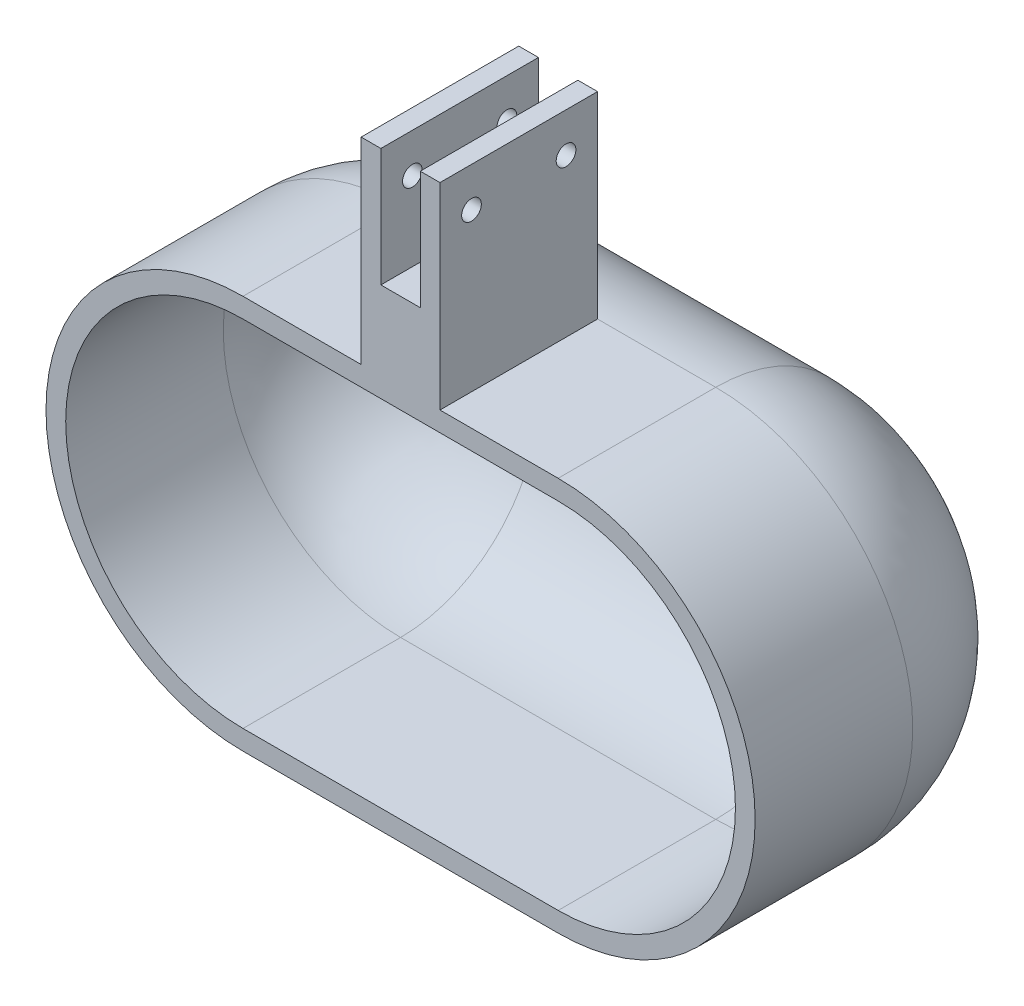
SolidWorks part; units mm, degrees
ref_plane "Front Plane" through (0, 0, 0) normal (0, 0, 1) x (1, 0, 0)
ref_plane "Top Plane" through (0, 0, 0) normal (0, 1, 0) x (1, 0, 0)
ref_plane "Right Plane" through (0, 0, 0) normal (1, 0, 0) x (0, 0, -1)
sketch "Sketch2" plane through (0, 0, 0) normal (0, 0, 1) x (1, 0, 0)
  line L0 (0, 0) -> (-80, 0) construction
  line L1 (0, -50) -> (-80, -50)
  line L2 (0, 50) -> (-80, 50)
  arc A0 (0, -50) -> (0, 50) centre (0, 0) ccw
  arc A1 (-80, 50) -> (-80, -50) centre (-80, 0) ccw
  point P3 (-40, 0)
  dimension "D1" = 100
  dimension "D2" = 80
extrude "Boss-Extrude1" add sketch "Sketch2" along normal blind 80
fillet "Fillet1" radius 40 4 edges at (-40, 50, 0) (-130, 0, 0) (-40, -50, 0) (50, 0, 0)
shell "Shell1" thickness 5
sketch "Sketch3" plane through (0, 50, 0) normal (0, 1, 0) x (1, 0, 0)
  line L0 (0, -80) -> (-80, -80) construction
  line L1 (-30, -80) -> (-50, -80)
  line L2 (-30, -80) -> (-30, -40)
  line L3 (-30, -40) -> (-50, -40)
  line L4 (-50, -80) -> (-50, -40)
  line L5 (0, -40) -> (-80, -40) construction
  line L6 (-40, 0) -> (-40, -40) construction
  line L7 (-80, 0) -> (0, 0) construction
  dimension "D1" = 20
extrude "Boss-Extrude2" add sketch "Sketch3" along normal blind 50
sketch "Sketch4" plane through (0, 100, 0) normal (0, 1, 0) x (1, 0, 0)
  line L0 (-40, -40) -> (-40, -80)
  line L1 (-30, -40) -> (-50, -40) construction
  line L2 (-50, -80) -> (-30, -80) construction
extrude "Cut-Extrude-Thin1" cut sketch "Sketch4" against normal blind 30 and the other way through all thin thin type mid plane wall 10
sketch "Sketch5" plane through (-30, 0, 0) normal (1, 0, 0) x (0, 0, -1)
  line L0 (-80, 90) -> (-40, 90) construction
  line L1 (-80, 100) -> (-80, 50) construction
  line L2 (-40, 100) -> (-40, 50) construction
  line L3 (-80, 100) -> (-40, 100) construction
  circle A0 centre (-72, 90) radius 2.5
  circle A1 centre (-48, 90) radius 2.5
  dimension "D3" = 8
  dimension "D4" = 5
  dimension "D1" = 10
  dimension "D2" = 8
extrude "Cut-Extrude1" cut sketch "Sketch5" against normal blind 92
sketch3d "3DSketch1"
  line L0 (-45, 90, 72) -> (-35, 90, 72)
  line L1 (-50, 90, 72) -> (-45, 90, 72) construction
  line L2 (-35, 90, 72) -> (-30, 90, 72) construction
  line L3 (-45, 90, 48) -> (-35, 90, 48)
  line L4 (-50, 90, 48) -> (-45, 90, 48) construction
  line L5 (-35, 90, 48) -> (-30, 90, 48) construction
  point P12 (-40, 90, 72)
  point P13 (-40, 90, 48)
